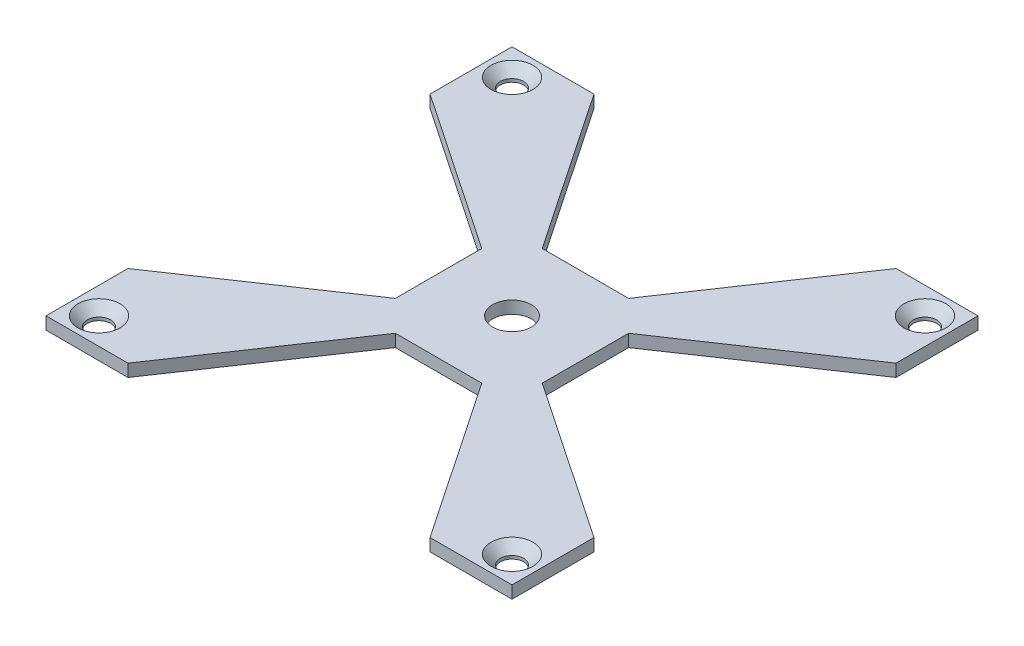
SolidWorks part; units mm, degrees
material "ABS"
ref_plane "Front Plane" through (0, 0, 0) normal (0, 0, 1) x (1, 0, 0)
ref_plane "Top Plane" through (0, 0, 0) normal (0, 1, 0) x (1, 0, 0)
ref_plane "Right Plane" through (0, 0, 0) normal (1, 0, 0) x (0, 0, -1)
sketch "Sketch1" plane through (0, 0, 0) normal (0, 1, 0) x (1, 0, 0)
  line L1 (-47.625, 47.625) -> (47.625, 47.625)
  line L2 (-47.625, 47.625) -> (-47.625, -47.625)
  line L3 (-47.625, -47.625) -> (47.625, -47.625)
  line L4 (47.625, 47.625) -> (47.625, -47.625)
  line L5 (-47.625, 47.625) -> (47.625, -47.625) construction
  line L6 (-47.625, -47.625) -> (47.625, 47.625) construction
  point P0 (0, 0)
  dimension "D1" = 95.25
  dimension "D2" = 95.25
extrude "Base Extrude" add sketch "Sketch1" along normal blind 2.54
sketch "Mounting Spots" plane through (0, 2.54, 0) normal (0, 1, 0) x (1, 0, 0)
  line L0 (-47.625, 47.625) -> (47.625, -47.625) construction
  line L1 (-47.625, -47.625) -> (47.625, 47.625) construction
  line L3 (47.625, -47.625) -> (47.625, 47.625) construction
  circle A0 centre (0, 0) radius 59.69 construction
  circle A1 centre (42.2072, 42.2072) radius 3.8405
  circle A2 centre (-42.2072, 42.2072) radius 3.8405
  circle A3 centre (-42.2072, -42.2072) radius 3.8405
  circle A4 centre (42.2072, -42.2072) radius 3.8405
  dimension "D1" = 119.38
  dimension "D2" = 7.681
hole_wizard "3/16 (0.1875) Diameter Hole1" positions "Sketch7" profile "Sketch8" hole size "3/16" standard "ANSI Inch"
sketch "Sketch7" plane through (0, 2.54, 0) normal (0, 1, 0) x (1, 0, 0)
  point P0 (-42.2072, 42.2072)
  point P3 (42.2072, 42.2072)
  point P6 (42.2072, -42.2072)
  point P9 (-42.2072, -42.2072)
sketch "Sketch8" plane through (-42.2072, 2.54, -42.2072) normal (1, 0, 0) x (0, 0, 1)
  line L0 (0, 0) -> (0, 3.9708)
  line L1 (0, 3.9708) -> (2.3812, 2.54)
  line L2 (2.3812, 2.54) -> (2.3812, 0)
  line L5 (2.3812, 0) -> (0, 0)
  line L10 (0, 3.9708) -> (-2.3812, 2.54) construction
  line L11 (0, -6.35) -> (0, 107.95) construction
  dimension "Hole Dia." = 4.7625
  dimension "Hole Depth" = 2.54
  dimension "Drill Angle" = 118
sketch "Sketch12" plane through (0, 2.54, 0) normal (0, 1, 0) x (1, 0, 0)
  line L0 (-47.625, 0) -> (47.625, 0) construction
  line L1 (-47.625, 47.625) -> (-47.625, -47.625) construction
  line L2 (47.625, -47.625) -> (47.625, 47.625) construction
  line L3 (0, 47.625) -> (0, -47.625) construction
  line L4 (47.625, 47.625) -> (-47.625, 47.625) construction
  line L5 (-47.625, -47.625) -> (47.625, -47.625) construction
  line L6 (-15.0063, 8.8308) -> (-15.0063, -8.8308)
  line L7 (-15.0063, 8.8308) -> (-47.625, 30.869)
  line L8 (-15.0063, -8.8308) -> (-47.625, -30.869)
  line L9 (-47.625, 30.869) -> (-47.625, -30.869)
  line L10 (30.869, 47.625) -> (-30.869, 47.625)
  line L11 (-8.8308, 15.0063) -> (-30.869, 47.625)
  line L12 (8.8308, 15.0063) -> (-8.8308, 15.0063)
  line L13 (8.8308, 15.0063) -> (30.869, 47.625)
  line L14 (47.625, -30.869) -> (47.625, 30.869)
  line L15 (15.0063, 8.8308) -> (47.625, 30.869)
  line L16 (15.0063, -8.8308) -> (15.0063, 8.8308)
  line L17 (15.0063, -8.8308) -> (47.625, -30.869)
  line L18 (-30.869, -47.625) -> (30.869, -47.625)
  line L19 (8.8308, -15.0063) -> (30.869, -47.625)
  line L20 (-8.8308, -15.0063) -> (8.8308, -15.0063)
  line L21 (-8.8308, -15.0063) -> (-30.869, -47.625)
  point P16 (-15.0063, 0)
  point P32 (0, 0)
  dimension "D1" = 17.6616
  dimension "D2" = 55.956
  dimension "D3" = 32.6187
  dimension "D4" = 4
extrude "Cut-Extrude1" cut sketch "Sketch12" against normal up to next
hole_wizard "5/16 (0.3125) Diameter Hole1" positions "Sketch13" profile "Sketch14" hole size "5/16" standard "ANSI Inch" end condition up to next
sketch "Sketch13" plane through (0, 2.54, 0) normal (0, 1, 0) x (1, 0, 0)
  point P0 (0, 0)
sketch "Sketch14" plane through (0, 2.54, 0) normal (1, 0, 0) x (0, 0, 1)
  line L0 (0, 0) -> (0, 2.54)
  line L1 (0, 2.54) -> (3.9688, 2.54)
  line L2 (3.9688, 2.54) -> (3.9687, 0)
  line L5 (3.9687, 0) -> (0, 0)
  line L11 (0, -6.35) -> (0, 107.95) construction
  dimension "Thru Hole Dia." = 7.9375
  dimension "Thru Hole Depth" = 2.54
chamfer "Chamfer1" distance 1.905 angle 45 4 edges at (-42.2072, 2.54, 44.5885) (42.2072, 2.54, 44.5885) (42.2072, 2.54, -39.826) (-42.2072, 2.54, -39.826)
equation "\"MSquare\"= 3.75"
equation "\"D1@Sketch1\"=\"MSquare\""
equation "\"D2@Sketch1\"=\"MSquare\""
equation "\"MountHoleDist\"= 4.7"
equation "\"D1@Mounting Spots\" = \"MountHoleDist\""
equation "\"MountHoleSize\"=0.302401"
equation "\"D2@Mounting Spots\" = \"MountHoleSize\""
